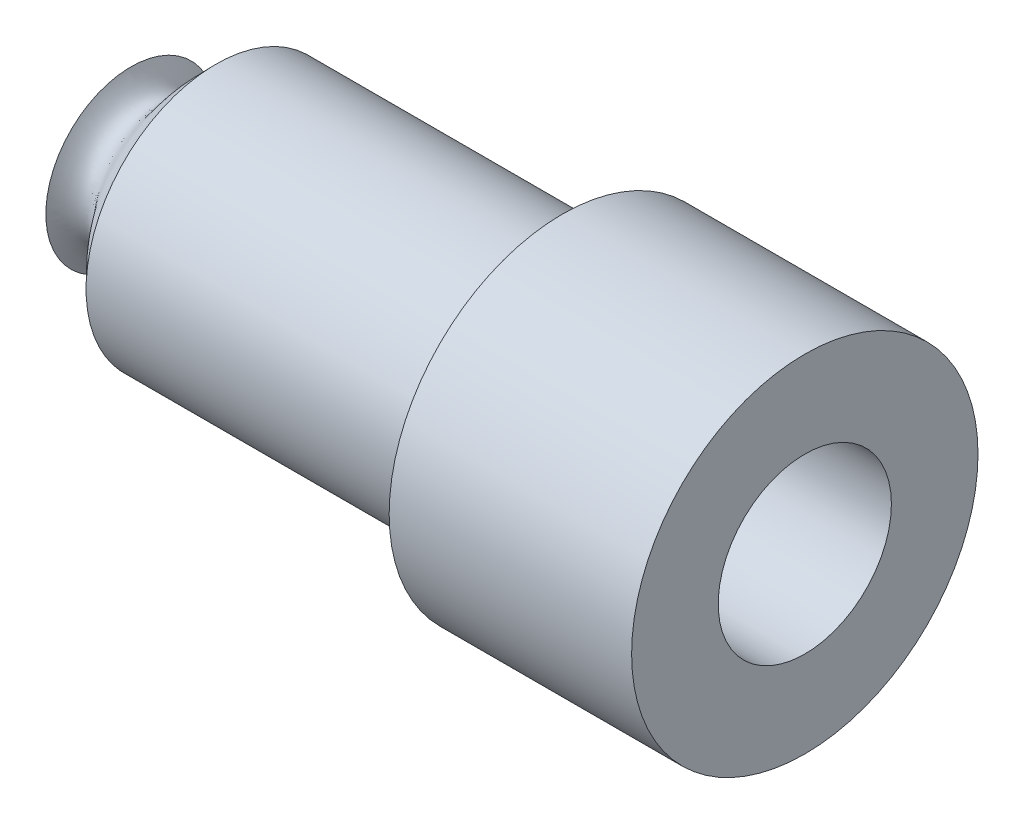
SolidWorks part; units mm, degrees
ref_plane "Front Plane" through (0, 0, 0) normal (1, 0, 0) x (0, 1, 0)
ref_plane "Top Plane" through (0, 0, 0) normal (0, 0, 1) x (0, 1, 0)
ref_plane "Right Plane" through (0, 0, 0) normal (0, 1, 0) x (-1, 0, 0)
sketch "Sketch3" plane through (0, 0, 0) normal (0, 1, 0) x (-1, 0, 0)
  line L0 (0, 2.5) -> (-20, 2.5)
  line L1 (-34, 5) -> (-20, 5)
  line L2 (-20, 2.5) -> (-20, 5)
  line L3 (-20, 7.5) -> (-20, 5)
  line L4 (-34, 5) -> (-34, 10)
  line L5 (-20, 7.5) -> (0, 7.5)
  line L6 (0, 2.5) -> (2.7569, 0.9083)
  line L7 (0, 0) -> (36.2796, 0) construction
  line L8 (3.3441, 0.7781) -> (4.9088, 0.915)
  line L9 (-34, 10) -> (-20, 10)
  line L10 (-20, 10) -> (-20, 7.5)
  line L11 (4.9088, 4.915) -> (4.9088, 0.915)
  arc A0 (2.7569, 0.9083) -> (3.3441, 0.7781) centre (3.2569, 1.7743) ccw
  spline S0 degree 3 poles (0, 7.5) (1.7529, 5.6648) (0.3738, 7.2403) (3.9056, 2.88) (4.9088, 4.915) knots 0 0 0 0 0.780983 1 1 1 1
  point P15 (3.03, 0.7506)
  point P17 (0, 0)
  dimension "D11" = 1
  dimension "D1" = 20
  dimension "D2" = 2.5
  dimension "D3" = 5
  dimension "D4" = 14
  dimension "D5" = 5
  dimension "D6" = 3.03
  dimension "D7" = 30
  dimension "D8" = 0.915
  dimension "D9" = 5
  dimension "D10" = 5
  dimension "D12" = 3
  dimension "D13" = 4
revolve "Revolve1" add sketch "Sketch3" angle 360 about L7
